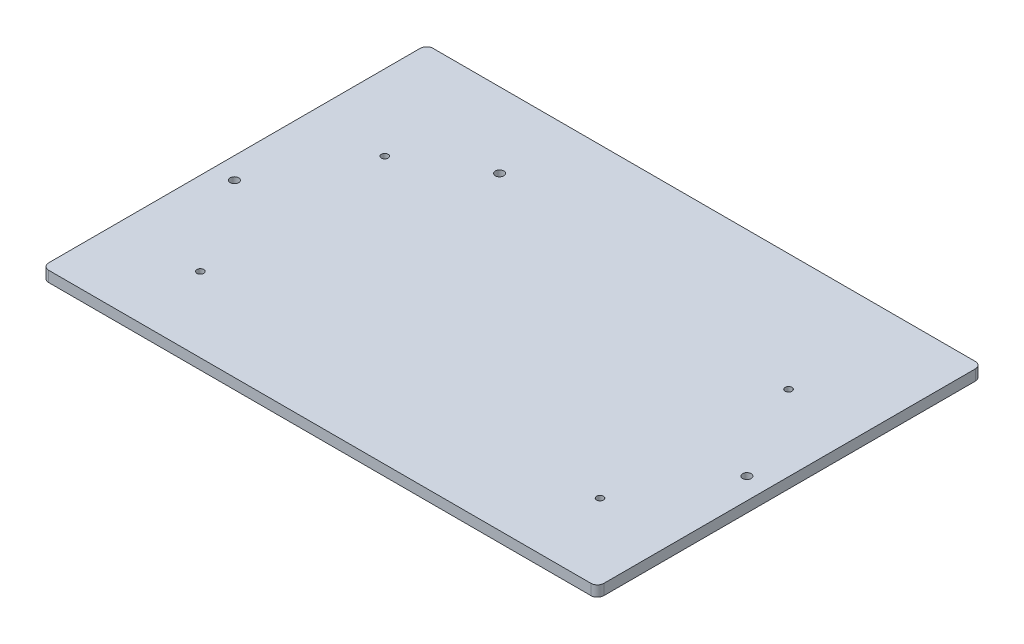
SolidWorks part; units mm, degrees
ref_plane "前视基准面" through (0, 0, 0) normal (0, 0, 1) x (1, 0, 0)
ref_plane "上视基准面" through (0, 0, 0) normal (0, 1, 0) x (1, 0, 0)
ref_plane "右视基准面" through (0, 0, 0) normal (1, 0, 0) x (0, 0, -1)
sketch "草图1" plane through (0, 0, 0) normal (0, 1, 0) x (1, 0, 0)
  line L1 (-124.9702, 64.1172) -> (135.0298, 64.1172)
  line L2 (-124.9702, 64.1172) -> (-124.9702, -115.8828)
  line L3 (-124.9702, -115.8828) -> (135.0298, -115.8828)
  line L4 (135.0298, 64.1172) -> (135.0298, -115.8828)
  circle A0 centre (-89.5202, 9.0772) radius 1.6
  circle A1 centre (99.5798, 9.0772) radius 1.6
  circle A2 centre (-85.9302, -80.8428) radius 1.6
  circle A3 centre (99.5798, -79.2001) radius 1.6
  circle A4 centre (-55.6397, 28.9874) radius 2
  circle A5 centre (-114.9702, -35.8828) radius 2
  circle A6 centre (125.0298, -35.8828) radius 2
  point P20 (0, 0)
  dimension "D3" = 3.2
  dimension "D4" = 3.2
  dimension "D5" = 3.2
  dimension "D6" = 3.2
  dimension "D9" = 89.92
  dimension "D14" = 4
  dimension "D15" = 4
  dimension "D16" = 4
  dimension "D1" = 260
  dimension "D2" = 180
  dimension "D7" = 189.1
  dimension "D8" = 3.59
  dimension "D10" = 185.51
  dimension "D11" = 0
  dimension "D12" = 55.04
  dimension "D13" = 35.45
  dimension "D17" = 10
  dimension "D18" = 10
  dimension "D19" = 100
  dimension "D20" = 100
extrude "凸台-拉伸1" add sketch "草图1" along normal blind 5
fillet "圆角1" radius 3 4 edges at (-124.9702, 2.5, -64.1172) (135.0298, 2.5, -64.1172) (135.0298, 2.5, 115.8828) (-124.9702, 2.5, 115.8828)
